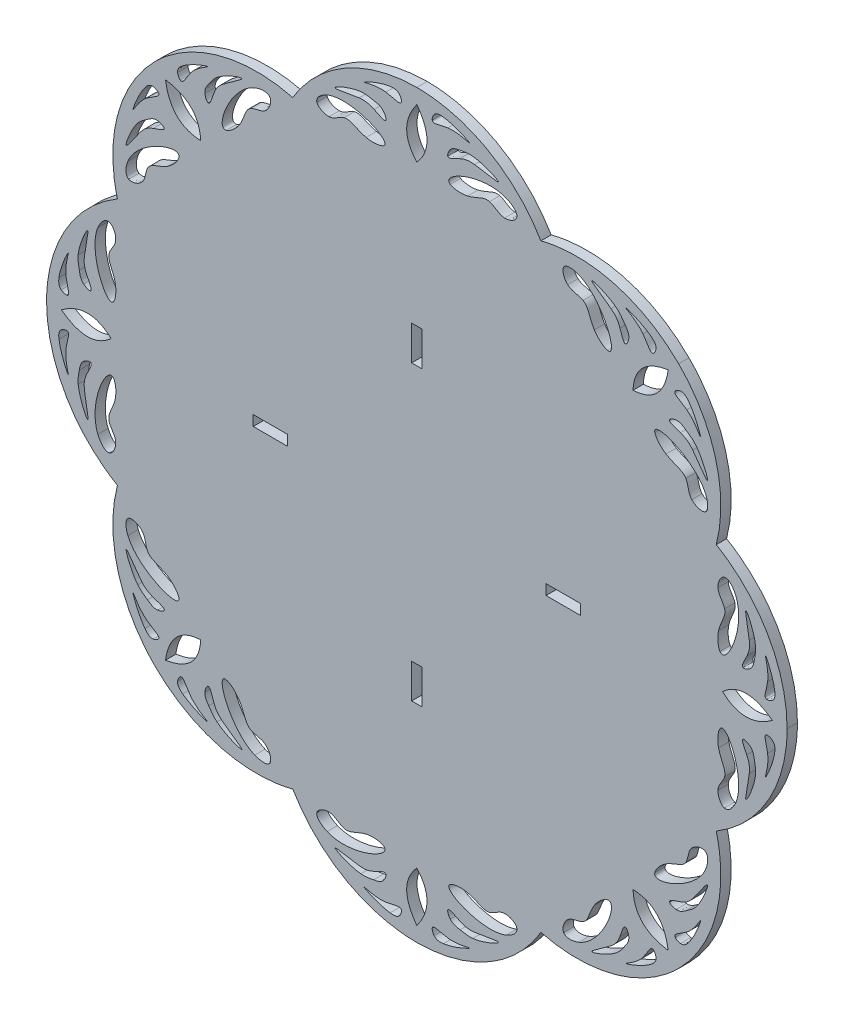
SolidWorks part; units mm, degrees
ref_plane "Plano frontal" through (0, 0, 0) normal (0, 0, 1) x (1, 0, 0)
ref_plane "Plano superior" through (0, 0, 0) normal (0, 1, 0) x (1, 0, 0)
ref_plane "Plano direito" through (0, 0, 0) normal (1, 0, 0) x (0, 0, -1)
sketch "Model" plane through (0, 0, 0) normal (0, 0, 1) x (1, 0, 0)
  line L58 (25.0001, 60.0569) -> (31.6667, 60.0569)
  line L59 (31.6667, 60.0569) -> (31.6667, 62.0569)
  line L60 (31.6667, 62.0569) -> (25.0001, 62.0569)
  line L61 (25.0001, 62.0569) -> (25.0001, 60.0569)
  line L62 (1.0001, 86.0569) -> (1.0001, 92.7236)
  line L63 (1.0001, 92.7236) -> (-0.9999, 92.7236)
  line L64 (-0.9999, 92.7236) -> (-0.9999, 86.0569)
  line L65 (-0.9999, 86.0569) -> (1.0001, 86.0569)
  line L66 (-31.6666, 60.0569) -> (-24.9999, 60.0569)
  line L67 (-24.9999, 60.0569) -> (-24.9999, 62.0569)
  line L68 (-24.9999, 62.0569) -> (-31.6666, 62.0569)
  line L69 (-31.6666, 62.0569) -> (-31.6666, 60.0569)
  line L70 (1.0001, 29.3903) -> (1.0001, 36.057)
  line L71 (1.0001, 36.057) -> (-0.9999, 36.057)
  line L72 (-0.9999, 36.057) -> (-0.9999, 29.3903)
  line L73 (-0.9999, 29.3903) -> (1.0001, 29.3903)
  line L74 (57.9547, 37.0512) -> (57.9546, 37.0513)
  spline S270 degree 3 poles (-52.2509, 104.8151) (-51.0841, 105.7149) (-49.5495, 106.2377) (-50.0038, 106.8337) knots 0 0 0 0 0.166667 0.166667 0.166667 0.166667
  spline S271 degree 3 poles (-50.0038, 106.8337) (-50.1747, 107.0579) (-50.6271, 107.2925) (-51.0214, 107.3395) knots 0.166667 0.166667 0.166667 0.166667 0.333333 0.333333 0.333333 0.333333
  spline S272 degree 3 poles (-51.0214, 107.3395) (-51.675, 107.4175) (-52.1689, 106.9805) (-52.6361, 106.3699) knots 0.333333 0.333333 0.333333 0.333333 0.5 0.5 0.5 0.5
  spline S273 degree 3 poles (-52.6361, 106.3699) (-53.9612, 104.6382) (-55.0714, 101.5111) (-54.917, 101.5396) knots 0.5 0.5 0.5 0.5 0.666667 0.666667 0.666667 0.666667
  spline S274 degree 3 poles (-54.917, 101.5396) (-54.795, 101.5621) (-53.8823, 103.557) (-52.2509, 104.8151) knots 0.666667 0.666667 0.666667 0.666667 1 1 1 1
  spline S275 degree 3 poles (-52.0754, 93.2206) (-51.4239, 94.3293) (-49.6775, 94.4625) (-48.2286, 95.3916) knots 0 0 0 0 0.142857 0.142857 0.142857 0.142857
  spline S276 degree 3 poles (-48.2286, 95.3916) (-47.1296, 96.0963) (-46.2019, 97.2589) (-46.0576, 97.9434) knots 0.142857 0.142857 0.142857 0.142857 0.285714 0.285714 0.285714 0.285714
  spline S277 degree 3 poles (-46.0576, 97.9434) (-45.5709, 100.253) (-54.0055, 97.1175) (-55.9222, 92.4208) knots 0.285714 0.285714 0.285714 0.285714 0.428571 0.428571 0.428571 0.428571
  spline S278 degree 3 poles (-55.9222, 92.4208) (-56.4254, 91.1875) (-56.4794, 89.8466) (-55.7668, 89.4564) knots 0.428571 0.428571 0.428571 0.428571 0.571429 0.571429 0.571429 0.571429
  spline S279 degree 3 poles (-55.7668, 89.4564) (-55.1261, 89.1054) (-53.8656, 89.5232) (-53.218, 90.2498) knots 0.571429 0.571429 0.571429 0.571429 0.714286 0.714286 0.714286 0.714286
  spline S280 degree 3 poles (-53.218, 90.2498) (-52.4458, 91.1162) (-52.5449, 92.4217) (-52.0754, 93.2206) knots 0.714286 0.714286 0.714286 0.714286 1 1 1 1
  spline S281 degree 3 poles (-32.1751, 113.1209) (-31.3762, 113.5904) (-30.0707, 113.4913) (-29.2043, 114.2635) knots 0 0 0 0 0.142857 0.142857 0.142857 0.142857
  spline S282 degree 3 poles (-29.2043, 114.2635) (-28.4777, 114.9111) (-28.0598, 116.1716) (-28.4109, 116.8123) knots 0.142857 0.142857 0.142857 0.142857 0.285714 0.285714 0.285714 0.285714
  spline S283 degree 3 poles (-28.4109, 116.8123) (-28.8011, 117.5248) (-30.142, 117.4709) (-31.3753, 116.9677) knots 0.285714 0.285714 0.285714 0.285714 0.428571 0.428571 0.428571 0.428571
  spline S284 degree 3 poles (-31.3753, 116.9677) (-36.072, 115.051) (-39.2075, 106.6164) (-36.8979, 107.1032) knots 0.428571 0.428571 0.428571 0.428571 0.571429 0.571429 0.571429 0.571429
  spline S285 degree 3 poles (-36.8979, 107.1032) (-36.2135, 107.2473) (-35.0508, 108.1751) (-34.3461, 109.2741) knots 0.571429 0.571429 0.571429 0.571429 0.714286 0.714286 0.714286 0.714286
  spline S286 degree 3 poles (-34.3461, 109.2741) (-33.417, 110.7229) (-33.2838, 112.4693) (-32.1751, 113.1209) knots 0.714286 0.714286 0.714286 0.714286 1 1 1 1
  spline S287 degree 3 poles (-43.7696, 113.2964) (-42.5115, 114.9278) (-40.5165, 115.8405) (-40.4941, 115.9625) knots 0 0 0 0 0.166667 0.166667 0.166667 0.166667
  spline S288 degree 3 poles (-40.4941, 115.9625) (-40.4657, 116.1169) (-43.5927, 115.0068) (-45.3243, 113.6817) knots 0.166667 0.166667 0.166667 0.166667 0.333333 0.333333 0.333333 0.333333
  spline S289 degree 3 poles (-45.3243, 113.6817) (-45.9349, 113.2144) (-46.372, 112.7205) (-46.2941, 112.0669) knots 0.333333 0.333333 0.333333 0.333333 0.5 0.5 0.5 0.5
  spline S290 degree 3 poles (-46.2941, 112.0669) (-46.247, 111.6726) (-46.0124, 111.2202) (-45.7882, 111.0493) knots 0.5 0.5 0.5 0.5 0.666667 0.666667 0.666667 0.666667
  spline S291 degree 3 poles (-45.7882, 111.0493) (-45.1922, 110.595) (-44.6694, 112.1296) (-43.7696, 113.2964) knots 0.666667 0.666667 0.666667 0.666667 1 1 1 1
  spline S292 degree 3 poles (-65.3251, 52.6691) (-65.4687, 51.8708) (-65.6418, 51.1534) (-65.5495, 50.2005) knots 0 0 0 0 0.125 0.125 0.125 0.125
  spline S293 degree 3 poles (-65.5495, 50.2005) (-65.3525, 48.1667) (-63.9461, 45.0602) (-63.6955, 45.2451) knots 0.125 0.125 0.125 0.125 0.25 0.25 0.25 0.25
  spline S294 degree 3 poles (-63.6955, 45.2451) (-63.4739, 45.4086) (-64.1556, 48.1441) (-64.3418, 49.8773) knots 0.25 0.25 0.25 0.25 0.375 0.375 0.375 0.375
  spline S295 degree 3 poles (-64.3418, 49.8773) (-64.4592, 50.9701) (-64.3797, 51.6644) (-63.857, 52.786) knots 0.375 0.375 0.375 0.375 0.5 0.5 0.5 0.5
  spline S296 degree 3 poles (-63.857, 52.786) (-63.4373, 53.6866) (-62.7316, 54.8628) (-63.1568, 55.0482) knots 0.5 0.5 0.5 0.5 0.625 0.625 0.625 0.625
  spline S297 degree 3 poles (-63.1568, 55.0482) (-63.4115, 55.1593) (-64.0717, 54.9149) (-64.4915, 54.5685) knots 0.625 0.625 0.625 0.625 0.75 0.75 0.75 0.75
  spline S298 degree 3 poles (-64.4915, 54.5685) (-65.1055, 54.062) (-65.205, 53.3372) (-65.3251, 52.6691) knots 0.75 0.75 0.75 0.75 1 1 1 1
  spline S299 degree 3 poles (-65.3251, 69.4217) (-65.205, 68.7537) (-65.1055, 68.0289) (-64.4915, 67.5224) knots 0 0 0 0 0.125 0.125 0.125 0.125
  spline S300 degree 3 poles (-64.4915, 67.5224) (-64.0717, 67.176) (-63.4115, 66.9316) (-63.1568, 67.0427) knots 0.125 0.125 0.125 0.125 0.25 0.25 0.25 0.25
  spline S301 degree 3 poles (-63.1568, 67.0427) (-62.7316, 67.2281) (-63.4373, 68.4042) (-63.857, 69.3049) knots 0.25 0.25 0.25 0.25 0.375 0.375 0.375 0.375
  spline S302 degree 3 poles (-63.857, 69.3049) (-64.3797, 70.4264) (-64.4592, 71.1208) (-64.3418, 72.2135) knots 0.375 0.375 0.375 0.375 0.5 0.5 0.5 0.5
  spline S303 degree 3 poles (-64.3418, 72.2135) (-64.1556, 73.9468) (-63.4739, 76.6823) (-63.6955, 76.8458) knots 0.5 0.5 0.5 0.5 0.625 0.625 0.625 0.625
  spline S304 degree 3 poles (-63.6955, 76.8458) (-63.9461, 77.0307) (-65.3525, 73.9242) (-65.5495, 71.8904) knots 0.625 0.625 0.625 0.625 0.75 0.75 0.75 0.75
  spline S305 degree 3 poles (-65.5495, 71.8904) (-65.6418, 70.9375) (-65.4687, 70.2201) (-65.3251, 69.4217) knots 0.75 0.75 0.75 0.75 1 1 1 1
  spline S306 degree 3 poles (-43.7696, 8.7945) (-44.6694, 9.9613) (-45.1922, 11.4959) (-45.7882, 11.0416) knots 0 0 0 0 0.166667 0.166667 0.166667 0.166667
  spline S307 degree 3 poles (-45.7882, 11.0416) (-46.0124, 10.8707) (-46.247, 10.4182) (-46.2941, 10.0239) knots 0.166667 0.166667 0.166667 0.166667 0.333333 0.333333 0.333333 0.333333
  spline S308 degree 3 poles (-46.2941, 10.0239) (-46.372, 9.3704) (-45.9349, 8.8765) (-45.3243, 8.4092) knots 0.333333 0.333333 0.333333 0.333333 0.5 0.5 0.5 0.5
  spline S309 degree 3 poles (-45.3243, 8.4092) (-43.5927, 7.0841) (-40.4657, 5.974) (-40.4941, 6.1284) knots 0.5 0.5 0.5 0.5 0.666667 0.666667 0.666667 0.666667
  spline S310 degree 3 poles (-40.4941, 6.1284) (-40.5165, 6.2504) (-42.5115, 7.163) (-43.7696, 8.7945) knots 0.666667 0.666667 0.666667 0.666667 1 1 1 1
  spline S311 degree 3 poles (-32.1751, 8.97) (-33.2838, 9.6215) (-33.417, 11.368) (-34.3461, 12.8168) knots 0 0 0 0 0.142857 0.142857 0.142857 0.142857
  spline S312 degree 3 poles (-34.3461, 12.8168) (-35.0508, 13.9158) (-36.2135, 14.8436) (-36.8979, 14.9877) knots 0.142857 0.142857 0.142857 0.142857 0.285714 0.285714 0.285714 0.285714
  spline S313 degree 3 poles (-36.8979, 14.9877) (-39.2075, 15.4745) (-36.072, 7.0399) (-31.3753, 5.1232) knots 0.285714 0.285714 0.285714 0.285714 0.428571 0.428571 0.428571 0.428571
  spline S314 degree 3 poles (-31.3753, 5.1232) (-30.142, 4.6199) (-28.8011, 4.5661) (-28.4109, 5.2785) knots 0.428571 0.428571 0.428571 0.428571 0.571429 0.571429 0.571429 0.571429
  spline S315 degree 3 poles (-28.4109, 5.2785) (-28.0598, 5.9193) (-28.4777, 7.1798) (-29.2043, 7.8274) knots 0.571429 0.571429 0.571429 0.571429 0.714286 0.714286 0.714286 0.714286
  spline S316 degree 3 poles (-29.2043, 7.8274) (-30.0707, 8.5996) (-31.3762, 8.5005) (-32.1751, 8.97) knots 0.714286 0.714286 0.714286 0.714286 1 1 1 1
  spline S317 degree 3 poles (-52.0754, 28.8702) (-52.5449, 29.6692) (-52.4458, 30.9747) (-53.218, 31.8411) knots 0 0 0 0 0.142857 0.142857 0.142857 0.142857
  spline S318 degree 3 poles (-53.218, 31.8411) (-53.8656, 32.5677) (-55.1261, 32.9855) (-55.7668, 32.6345) knots 0.142857 0.142857 0.142857 0.142857 0.285714 0.285714 0.285714 0.285714
  spline S319 degree 3 poles (-55.7668, 32.6345) (-56.4794, 32.2443) (-56.4254, 30.9034) (-55.9222, 29.6701) knots 0.285714 0.285714 0.285714 0.285714 0.428571 0.428571 0.428571 0.428571
  spline S320 degree 3 poles (-55.9222, 29.6701) (-54.0055, 24.9733) (-45.5709, 21.8379) (-46.0576, 24.1474) knots 0.428571 0.428571 0.428571 0.428571 0.571429 0.571429 0.571429 0.571429
  spline S321 degree 3 poles (-46.0576, 24.1474) (-46.2019, 24.8319) (-47.1296, 25.9946) (-48.2286, 26.6993) knots 0.571429 0.571429 0.571429 0.571429 0.714286 0.714286 0.714286 0.714286
  spline S322 degree 3 poles (-48.2286, 26.6993) (-49.6775, 27.6284) (-51.4239, 27.7616) (-52.0754, 28.8702) knots 0.714286 0.714286 0.714286 0.714286 1 1 1 1
  spline S323 degree 3 poles (-52.2509, 17.2758) (-53.8823, 18.5339) (-54.795, 20.5288) (-54.917, 20.5513) knots 0 0 0 0 0.166667 0.166667 0.166667 0.166667
  spline S324 degree 3 poles (-54.917, 20.5513) (-55.0714, 20.5797) (-53.9612, 17.4526) (-52.6361, 15.721) knots 0.166667 0.166667 0.166667 0.166667 0.333333 0.333333 0.333333 0.333333
  spline S325 degree 3 poles (-52.6361, 15.721) (-52.1689, 15.1104) (-51.675, 14.6734) (-51.0214, 14.7514) knots 0.333333 0.333333 0.333333 0.333333 0.5 0.5 0.5 0.5
  spline S326 degree 3 poles (-51.0214, 14.7514) (-50.6271, 14.7984) (-50.1747, 15.033) (-50.0038, 15.2572) knots 0.5 0.5 0.5 0.5 0.666667 0.666667 0.666667 0.666667
  spline S327 degree 3 poles (-50.0038, 15.2572) (-49.5495, 15.8531) (-51.0841, 16.376) (-52.2509, 17.2758) knots 0.666667 0.666667 0.666667 0.666667 1 1 1 1
  spline S328 degree 3 poles (8.3763, -4.2797) (9.1747, -4.4233) (9.8921, -4.5965) (10.845, -4.5042) knots 0 0 0 0 0.125 0.125 0.125 0.125
  spline S329 degree 3 poles (10.845, -4.5042) (12.8788, -4.3071) (15.9853, -2.9007) (15.8004, -2.65) knots 0.125 0.125 0.125 0.125 0.25 0.25 0.25 0.25
  spline S330 degree 3 poles (15.8004, -2.65) (15.6369, -2.4285) (12.9014, -3.1101) (11.1681, -3.2964) knots 0.25 0.25 0.25 0.25 0.375 0.375 0.375 0.375
  spline S331 degree 3 poles (11.1681, -3.2964) (10.0754, -3.4138) (9.3811, -3.3343) (8.2595, -2.8117) knots 0.375 0.375 0.375 0.375 0.5 0.5 0.5 0.5
  spline S332 degree 3 poles (8.2595, -2.8117) (7.3588, -2.3919) (6.1826, -1.6862) (5.9973, -2.1114) knots 0.5 0.5 0.5 0.5 0.625 0.625 0.625 0.625
  spline S333 degree 3 poles (5.9973, -2.1114) (5.8862, -2.3661) (6.1306, -3.0264) (6.477, -3.4461) knots 0.625 0.625 0.625 0.625 0.75 0.75 0.75 0.75
  spline S334 degree 3 poles (6.477, -3.4461) (6.9835, -4.0601) (7.7083, -4.1595) (8.3763, -4.2797) knots 0.75 0.75 0.75 0.75 1 1 1 1
  spline S335 degree 3 poles (-8.3762, -4.2797) (-7.7082, -4.1595) (-6.9834, -4.0601) (-6.4769, -3.4461) knots 0 0 0 0 0.125 0.125 0.125 0.125
  spline S336 degree 3 poles (-6.4769, -3.4461) (-6.1305, -3.0264) (-5.8861, -2.3661) (-5.9972, -2.1114) knots 0.125 0.125 0.125 0.125 0.25 0.25 0.25 0.25
  spline S337 degree 3 poles (-5.9972, -2.1114) (-6.1826, -1.6862) (-7.3587, -2.3919) (-8.2594, -2.8117) knots 0.25 0.25 0.25 0.25 0.375 0.375 0.375 0.375
  spline S338 degree 3 poles (-8.2594, -2.8117) (-9.3809, -3.3343) (-10.0753, -3.4138) (-11.1681, -3.2964) knots 0.375 0.375 0.375 0.375 0.5 0.5 0.5 0.5
  spline S339 degree 3 poles (-11.1681, -3.2964) (-12.9013, -3.1101) (-15.6368, -2.4285) (-15.8003, -2.65) knots 0.5 0.5 0.5 0.5 0.625 0.625 0.625 0.625
  spline S340 degree 3 poles (-15.8003, -2.65) (-15.9852, -2.9007) (-12.8787, -4.3071) (-10.8449, -4.5042) knots 0.625 0.625 0.625 0.625 0.75 0.75 0.75 0.75
  spline S341 degree 3 poles (-10.8449, -4.5042) (-9.892, -4.5965) (-9.1746, -4.4233) (-8.3762, -4.2797) knots 0.75 0.75 0.75 0.75 1 1 1 1
  spline S342 degree 3 poles (52.251, 17.2758) (51.0842, 16.376) (49.5496, 15.8531) (50.0039, 15.2572) knots 0 0 0 0 0.166667 0.166667 0.166667 0.166667
  spline S343 degree 3 poles (50.0039, 15.2572) (50.1748, 15.033) (50.6272, 14.7984) (51.0215, 14.7514) knots 0.166667 0.166667 0.166667 0.166667 0.333333 0.333333 0.333333 0.333333
  spline S344 degree 3 poles (51.0215, 14.7514) (51.6751, 14.6734) (52.169, 15.1104) (52.6362, 15.721) knots 0.333333 0.333333 0.333333 0.333333 0.5 0.5 0.5 0.5
  spline S345 degree 3 poles (52.6362, 15.721) (53.9613, 17.4526) (55.0715, 20.5797) (54.9171, 20.5513) knots 0.5 0.5 0.5 0.5 0.666667 0.666667 0.666667 0.666667
  spline S346 degree 3 poles (54.9171, 20.5513) (54.7951, 20.5288) (53.8825, 18.5339) (52.251, 17.2758) knots 0.666667 0.666667 0.666667 0.666667 1 1 1 1
  spline S347 degree 3 poles (52.0755, 28.8702) (51.424, 27.7616) (49.6776, 27.6284) (48.2287, 26.6993) knots 0 0 0 0 0.142857 0.142857 0.142857 0.142857
  spline S348 degree 3 poles (48.2287, 26.6993) (47.1297, 25.9946) (46.202, 24.8319) (46.0577, 24.1474) knots 0.142857 0.142857 0.142857 0.142857 0.285714 0.285714 0.285714 0.285714
  spline S349 degree 3 poles (46.0577, 24.1474) (45.571, 21.8379) (54.0056, 24.9733) (55.9223, 29.6701) knots 0.285714 0.285714 0.285714 0.285714 0.428571 0.428571 0.428571 0.428571
  spline S350 degree 3 poles (55.9223, 29.6701) (56.4256, 30.9034) (56.4795, 32.2443) (55.7669, 32.6345) knots 0.428571 0.428571 0.428571 0.428571 0.571429 0.571429 0.571429 0.571429
  spline S351 degree 3 poles (55.7669, 32.6345) (55.1262, 32.9855) (53.8657, 32.5677) (53.2181, 31.8411) knots 0.571429 0.571429 0.571429 0.571429 0.714286 0.714286 0.714286 0.714286
  spline S352 degree 3 poles (53.2181, 31.8411) (52.4459, 30.9747) (52.545, 29.6692) (52.0755, 28.8702) knots 0.714286 0.714286 0.714286 0.714286 1 1 1 1
  spline S353 degree 3 poles (32.1752, 8.97) (31.3763, 8.5005) (30.0709, 8.5996) (29.2044, 7.8274) knots 0 0 0 0 0.142857 0.142857 0.142857 0.142857
  spline S354 degree 3 poles (29.2044, 7.8274) (28.4778, 7.1798) (28.0599, 5.9193) (28.4109, 5.2785) knots 0.142857 0.142857 0.142857 0.142857 0.285714 0.285714 0.285714 0.285714
  spline S355 degree 3 poles (28.4109, 5.2785) (28.8012, 4.5661) (30.1421, 4.6199) (31.3754, 5.1232) knots 0.285714 0.285714 0.285714 0.285714 0.428571 0.428571 0.428571 0.428571
  spline S356 degree 3 poles (31.3754, 5.1232) (36.0721, 7.0399) (39.2076, 15.4745) (36.898, 14.9877) knots 0.428571 0.428571 0.428571 0.428571 0.571429 0.571429 0.571429 0.571429
  spline S357 degree 3 poles (36.898, 14.9877) (36.2136, 14.8436) (35.0509, 13.9158) (34.3462, 12.8168) knots 0.571429 0.571429 0.571429 0.571429 0.714286 0.714286 0.714286 0.714286
  spline S358 degree 3 poles (34.3462, 12.8168) (33.417, 11.368) (33.2839, 9.6215) (32.1752, 8.97) knots 0.714286 0.714286 0.714286 0.714286 1 1 1 1
  spline S359 degree 3 poles (43.7697, 8.7945) (42.5116, 7.163) (40.5166, 6.2504) (40.4942, 6.1284) knots 0 0 0 0 0.166667 0.166667 0.166667 0.166667
  spline S360 degree 3 poles (40.4942, 6.1284) (40.4658, 5.974) (43.5928, 7.0841) (45.3244, 8.4092) knots 0.166667 0.166667 0.166667 0.166667 0.333333 0.333333 0.333333 0.333333
  spline S361 degree 3 poles (45.3244, 8.4092) (45.935, 8.8765) (46.3721, 9.3704) (46.2941, 10.0239) knots 0.333333 0.333333 0.333333 0.333333 0.5 0.5 0.5 0.5
  spline S362 degree 3 poles (46.2941, 10.0239) (46.2471, 10.4182) (46.0125, 10.8707) (45.7883, 11.0416) knots 0.5 0.5 0.5 0.5 0.666667 0.666667 0.666667 0.666667
  spline S363 degree 3 poles (45.7883, 11.0416) (45.1923, 11.4959) (44.6694, 9.9613) (43.7697, 8.7945) knots 0.666667 0.666667 0.666667 0.666667 1 1 1 1
  spline S364 degree 3 poles (65.3252, 69.4217) (65.4688, 70.2201) (65.6419, 70.9375) (65.5496, 71.8904) knots 0 0 0 0 0.125 0.125 0.125 0.125
  spline S365 degree 3 poles (65.5496, 71.8904) (65.3526, 73.9242) (63.9462, 77.0307) (63.6955, 76.8458) knots 0.125 0.125 0.125 0.125 0.25 0.25 0.25 0.25
  spline S366 degree 3 poles (63.6955, 76.8458) (63.474, 76.6823) (64.1556, 73.9468) (64.3419, 72.2135) knots 0.25 0.25 0.25 0.25 0.375 0.375 0.375 0.375
  spline S367 degree 3 poles (64.3419, 72.2135) (64.4593, 71.1208) (64.3798, 70.4264) (63.8571, 69.3049) knots 0.375 0.375 0.375 0.375 0.5 0.5 0.5 0.5
  spline S368 degree 3 poles (63.8571, 69.3049) (63.4373, 68.4042) (62.7317, 67.2281) (63.1569, 67.0427) knots 0.5 0.5 0.5 0.5 0.625 0.625 0.625 0.625
  spline S369 degree 3 poles (63.1569, 67.0427) (63.4116, 66.9316) (64.0718, 67.176) (64.4916, 67.5224) knots 0.625 0.625 0.625 0.625 0.75 0.75 0.75 0.75
  spline S370 degree 3 poles (64.4916, 67.5224) (65.1055, 68.0289) (65.2051, 68.7537) (65.3252, 69.4217) knots 0.75 0.75 0.75 0.75 1 1 1 1
  spline S371 degree 3 poles (65.3252, 52.6691) (65.2051, 53.3372) (65.1055, 54.062) (64.4916, 54.5685) knots 0 0 0 0 0.125 0.125 0.125 0.125
  spline S372 degree 3 poles (64.4916, 54.5685) (64.0718, 54.9149) (63.4116, 55.1593) (63.1569, 55.0482) knots 0.125 0.125 0.125 0.125 0.25 0.25 0.25 0.25
  spline S373 degree 3 poles (63.1569, 55.0482) (62.7317, 54.8628) (63.4373, 53.6866) (63.8571, 52.786) knots 0.25 0.25 0.25 0.25 0.375 0.375 0.375 0.375
  spline S374 degree 3 poles (63.8571, 52.786) (64.3798, 51.6644) (64.4593, 50.9701) (64.3419, 49.8773) knots 0.375 0.375 0.375 0.375 0.5 0.5 0.5 0.5
  spline S375 degree 3 poles (64.3419, 49.8773) (64.1556, 48.1441) (63.474, 45.4086) (63.6955, 45.2451) knots 0.5 0.5 0.5 0.5 0.625 0.625 0.625 0.625
  spline S376 degree 3 poles (63.6955, 45.2451) (63.9462, 45.0602) (65.3526, 48.1667) (65.5496, 50.2005) knots 0.625 0.625 0.625 0.625 0.75 0.75 0.75 0.75
  spline S377 degree 3 poles (65.5496, 50.2005) (65.6419, 51.1534) (65.4688, 51.8708) (65.3252, 52.6691) knots 0.75 0.75 0.75 0.75 1 1 1 1
  spline S378 degree 3 poles (43.7697, 113.2964) (44.6694, 112.1296) (45.1923, 110.595) (45.7883, 111.0493) knots 0 0 0 0 0.166667 0.166667 0.166667 0.166667
  spline S379 degree 3 poles (45.7883, 111.0493) (46.0125, 111.2202) (46.2471, 111.6726) (46.2941, 112.0669) knots 0.166667 0.166667 0.166667 0.166667 0.333333 0.333333 0.333333 0.333333
  spline S380 degree 3 poles (46.2941, 112.0669) (46.3721, 112.7205) (45.935, 113.2144) (45.3244, 113.6817) knots 0.333333 0.333333 0.333333 0.333333 0.5 0.5 0.5 0.5
  spline S381 degree 3 poles (45.3244, 113.6817) (43.5928, 115.0068) (40.4658, 116.1169) (40.4942, 115.9625) knots 0.5 0.5 0.5 0.5 0.666667 0.666667 0.666667 0.666667
  spline S382 degree 3 poles (40.4942, 115.9625) (40.5166, 115.8405) (42.5116, 114.9278) (43.7697, 113.2964) knots 0.666667 0.666667 0.666667 0.666667 1 1 1 1
  spline S383 degree 3 poles (32.1752, 113.1209) (33.2839, 112.4693) (33.417, 110.7229) (34.3462, 109.2741) knots 0 0 0 0 0.142857 0.142857 0.142857 0.142857
  spline S384 degree 3 poles (34.3462, 109.2741) (35.0509, 108.1751) (36.2136, 107.2473) (36.898, 107.1032) knots 0.142857 0.142857 0.142857 0.142857 0.285714 0.285714 0.285714 0.285714
  spline S385 degree 3 poles (36.898, 107.1032) (39.2076, 106.6164) (36.0721, 115.051) (31.3754, 116.9677) knots 0.285714 0.285714 0.285714 0.285714 0.428571 0.428571 0.428571 0.428571
  spline S386 degree 3 poles (31.3754, 116.9677) (30.1421, 117.4709) (28.8012, 117.5248) (28.4109, 116.8123) knots 0.428571 0.428571 0.428571 0.428571 0.571429 0.571429 0.571429 0.571429
  spline S387 degree 3 poles (28.4109, 116.8123) (28.0599, 116.1716) (28.4778, 114.9111) (29.2044, 114.2635) knots 0.571429 0.571429 0.571429 0.571429 0.714286 0.714286 0.714286 0.714286
  spline S388 degree 3 poles (29.2044, 114.2635) (30.0709, 113.4913) (31.3763, 113.5904) (32.1752, 113.1209) knots 0.714286 0.714286 0.714286 0.714286 1 1 1 1
  spline S389 degree 3 poles (52.0755, 93.2206) (52.545, 92.4217) (52.4459, 91.1162) (53.2181, 90.2498) knots 0 0 0 0 0.142857 0.142857 0.142857 0.142857
  spline S390 degree 3 poles (53.2181, 90.2498) (53.8657, 89.5232) (55.1262, 89.1054) (55.7669, 89.4564) knots 0.142857 0.142857 0.142857 0.142857 0.285714 0.285714 0.285714 0.285714
  spline S391 degree 3 poles (55.7669, 89.4564) (56.4795, 89.8466) (56.4256, 91.1875) (55.9223, 92.4208) knots 0.285714 0.285714 0.285714 0.285714 0.428571 0.428571 0.428571 0.428571
  spline S392 degree 3 poles (55.9223, 92.4208) (54.0056, 97.1175) (45.571, 100.253) (46.0577, 97.9434) knots 0.428571 0.428571 0.428571 0.428571 0.571429 0.571429 0.571429 0.571429
  spline S393 degree 3 poles (46.0577, 97.9434) (46.202, 97.2589) (47.1297, 96.0963) (48.2287, 95.3916) knots 0.571429 0.571429 0.571429 0.571429 0.714286 0.714286 0.714286 0.714286
  spline S394 degree 3 poles (48.2287, 95.3916) (49.6776, 94.4625) (51.424, 94.3293) (52.0755, 93.2206) knots 0.714286 0.714286 0.714286 0.714286 1 1 1 1
  spline S395 degree 3 poles (52.251, 104.8151) (53.8825, 103.557) (54.7951, 101.5621) (54.9171, 101.5396) knots 0 0 0 0 0.166667 0.166667 0.166667 0.166667
  spline S396 degree 3 poles (54.9171, 101.5396) (55.0715, 101.5111) (53.9613, 104.6382) (52.6362, 106.3699) knots 0.166667 0.166667 0.166667 0.166667 0.333333 0.333333 0.333333 0.333333
  spline S397 degree 3 poles (52.6362, 106.3699) (52.169, 106.9805) (51.6751, 107.4175) (51.0215, 107.3395) knots 0.333333 0.333333 0.333333 0.333333 0.5 0.5 0.5 0.5
  spline S398 degree 3 poles (51.0215, 107.3395) (50.6272, 107.2925) (50.1748, 107.0579) (50.0039, 106.8337) knots 0.5 0.5 0.5 0.5 0.666667 0.666667 0.666667 0.666667
  spline S399 degree 3 poles (50.0039, 106.8337) (49.5496, 106.2377) (51.0842, 105.7149) (52.251, 104.8151) knots 0.666667 0.666667 0.666667 0.666667 1 1 1 1
  spline S400 degree 3 poles (-8.3762, 126.3706) (-9.1746, 126.5142) (-9.892, 126.6873) (-10.8449, 126.5951) knots 0 0 0 0 0.125 0.125 0.125 0.125
  spline S401 degree 3 poles (-10.8449, 126.5951) (-12.8787, 126.398) (-15.9852, 124.9916) (-15.8003, 124.7409) knots 0.125 0.125 0.125 0.125 0.25 0.25 0.25 0.25
  spline S402 degree 3 poles (-15.8003, 124.7409) (-15.6368, 124.5194) (-12.9013, 125.201) (-11.1681, 125.3873) knots 0.25 0.25 0.25 0.25 0.375 0.375 0.375 0.375
  spline S403 degree 3 poles (-11.1681, 125.3873) (-10.0753, 125.5047) (-9.3809, 125.4252) (-8.2594, 124.9025) knots 0.375 0.375 0.375 0.375 0.5 0.5 0.5 0.5
  spline S404 degree 3 poles (-8.2594, 124.9025) (-7.3587, 124.4828) (-6.1826, 123.7771) (-5.9972, 124.2023) knots 0.5 0.5 0.5 0.5 0.625 0.625 0.625 0.625
  spline S405 degree 3 poles (-5.9972, 124.2023) (-5.8861, 124.457) (-6.1305, 125.1173) (-6.4769, 125.537) knots 0.625 0.625 0.625 0.625 0.75 0.75 0.75 0.75
  spline S406 degree 3 poles (-6.4769, 125.537) (-6.9834, 126.151) (-7.7082, 126.2504) (-8.3762, 126.3706) knots 0.75 0.75 0.75 0.75 1 1 1 1
  spline S407 degree 3 poles (8.3763, 126.3706) (7.7083, 126.2504) (6.9835, 126.151) (6.477, 125.537) knots 0 0 0 0 0.125 0.125 0.125 0.125
  spline S408 degree 3 poles (6.477, 125.537) (6.1306, 125.1173) (5.8862, 124.457) (5.9973, 124.2023) knots 0.125 0.125 0.125 0.125 0.25 0.25 0.25 0.25
  spline S409 degree 3 poles (5.9973, 124.2023) (6.1826, 123.7771) (7.3588, 124.4828) (8.2595, 124.9025) knots 0.25 0.25 0.25 0.25 0.375 0.375 0.375 0.375
  spline S410 degree 3 poles (8.2595, 124.9025) (9.3811, 125.4252) (10.0754, 125.5047) (11.1681, 125.3873) knots 0.375 0.375 0.375 0.375 0.5 0.5 0.5 0.5
  spline S411 degree 3 poles (11.1681, 125.3873) (12.9014, 125.201) (15.6369, 124.5194) (15.8004, 124.7409) knots 0.5 0.5 0.5 0.5 0.625 0.625 0.625 0.625
  spline S412 degree 3 poles (15.8004, 124.7409) (15.9853, 124.9916) (12.8788, 126.398) (10.845, 126.5951) knots 0.625 0.625 0.625 0.625 0.75 0.75 0.75 0.75
  spline S413 degree 3 poles (10.845, 126.5951) (9.8921, 126.6873) (9.1747, 126.5142) (8.3763, 126.3706) knots 0.75 0.75 0.75 0.75 1 1 1 1
  spline S414 degree 3 poles (5.9973, 128.9422) (8.0405, 129.2063) (10.0964, 128.4409) (10.1986, 128.5114) knots 0 0 0 0 0.166667 0.166667 0.166667 0.166667
  spline S415 degree 3 poles (10.1986, 128.5114) (10.3278, 128.6004) (7.3317, 130.0266) (5.1703, 130.3141) knots 0.166667 0.166667 0.166667 0.166667 0.333333 0.333333 0.333333 0.333333
  spline S416 degree 3 poles (5.1703, 130.3141) (4.4081, 130.4154) (3.7498, 130.3752) (3.3428, 129.8579) knots 0.333333 0.333333 0.333333 0.333333 0.5 0.5 0.5 0.5
  spline S417 degree 3 poles (3.3428, 129.8579) (3.0973, 129.5458) (2.9432, 129.0601) (2.9809, 128.7807) knots 0.5 0.5 0.5 0.5 0.666667 0.666667 0.666667 0.666667
  spline S418 degree 3 poles (2.9809, 128.7807) (3.0812, 128.038) (4.536, 128.7534) (5.9973, 128.9422) knots 0.666667 0.666667 0.666667 0.666667 1 1 1 1
  spline S419 degree 3 poles (14.0716, 120.6196) (14.9685, 120.3867) (15.8216, 119.3935) (16.9803, 119.3269) knots 0 0 0 0 0.142857 0.142857 0.142857 0.142857
  spline S420 degree 3 poles (16.9803, 119.3269) (17.952, 119.271) (19.1388, 119.8669) (19.3437, 120.5681) knots 0.142857 0.142857 0.142857 0.142857 0.285714 0.285714 0.285714 0.285714
  spline S421 degree 3 poles (19.3437, 120.5681) (19.5715, 121.3479) (18.5852, 122.2579) (17.3573, 122.7742) knots 0.285714 0.285714 0.285714 0.285714 0.428571 0.428571 0.428571 0.428571
  spline S422 degree 3 poles (17.3573, 122.7742) (12.6809, 124.7399) (4.4997, 120.9929) (6.477, 119.704) knots 0.428571 0.428571 0.428571 0.428571 0.571429 0.571429 0.571429 0.571429
  spline S423 degree 3 poles (6.477, 119.704) (7.0629, 119.322) (8.5411, 119.1558) (9.8165, 119.4346) knots 0.571429 0.571429 0.571429 0.571429 0.714286 0.714286 0.714286 0.714286
  spline S424 degree 3 poles (9.8165, 119.4346) (11.498, 119.8022) (12.827, 120.9429) (14.0716, 120.6196) knots 0.714286 0.714286 0.714286 0.714286 1 1 1 1
  spline S425 degree 3 poles (-14.0715, 120.6196) (-12.8269, 120.9429) (-11.4979, 119.8022) (-9.8164, 119.4346) knots 0 0 0 0 0.142857 0.142857 0.142857 0.142857
  spline S426 degree 3 poles (-9.8164, 119.4346) (-8.541, 119.1558) (-7.0628, 119.322) (-6.4769, 119.704) knots 0.142857 0.142857 0.142857 0.142857 0.285714 0.285714 0.285714 0.285714
  spline S427 degree 3 poles (-6.4769, 119.704) (-4.4996, 120.9929) (-12.6808, 124.7399) (-17.3572, 122.7742) knots 0.285714 0.285714 0.285714 0.285714 0.428571 0.428571 0.428571 0.428571
  spline S428 degree 3 poles (-17.3572, 122.7742) (-18.5851, 122.2579) (-19.5714, 121.3479) (-19.3436, 120.5681) knots 0.428571 0.428571 0.428571 0.428571 0.571429 0.571429 0.571429 0.571429
  spline S429 degree 3 poles (-19.3436, 120.5681) (-19.1387, 119.8669) (-17.9519, 119.271) (-16.9802, 119.3269) knots 0.571429 0.571429 0.571429 0.571429 0.714286 0.714286 0.714286 0.714286
  spline S430 degree 3 poles (-16.9802, 119.3269) (-15.8215, 119.3935) (-14.9684, 120.3867) (-14.0715, 120.6196) knots 0.714286 0.714286 0.714286 0.714286 1 1 1 1
  spline S431 degree 3 poles (-5.9972, 128.9422) (-4.5359, 128.7534) (-3.0811, 128.038) (-2.9808, 128.7807) knots 0 0 0 0 0.166667 0.166667 0.166667 0.166667
  spline S432 degree 3 poles (-2.9808, 128.7807) (-2.9431, 129.0601) (-3.0972, 129.5458) (-3.3427, 129.8579) knots 0.166667 0.166667 0.166667 0.166667 0.333333 0.333333 0.333333 0.333333
  spline S433 degree 3 poles (-3.3427, 129.8579) (-3.7497, 130.3752) (-4.408, 130.4154) (-5.1701, 130.3141) knots 0.333333 0.333333 0.333333 0.333333 0.5 0.5 0.5 0.5
  spline S434 degree 3 poles (-5.1701, 130.3141) (-7.3316, 130.0266) (-10.3278, 128.6004) (-10.1985, 128.5114) knots 0.5 0.5 0.5 0.5 0.666667 0.666667 0.666667 0.666667
  spline S435 degree 3 poles (-10.1985, 128.5114) (-10.0963, 128.4409) (-8.0404, 129.2063) (-5.9972, 128.9422) knots 0.666667 0.666667 0.666667 0.666667 1 1 1 1
  spline S436 degree 3 poles (52.1148, 101.3144) (51.5575, 101.7018) (50.9746, 102.1439) (50.1823, 102.068) knots 0 0 0 0 0.125 0.125 0.125 0.125
  spline S437 degree 3 poles (50.1823, 102.068) (49.6406, 102.0161) (49.0009, 101.722) (48.8994, 101.4634) knots 0.125 0.125 0.125 0.125 0.25 0.25 0.25 0.25
  spline S438 degree 3 poles (48.8994, 101.4634) (48.7298, 101.0317) (50.0605, 100.6989) (50.9942, 100.3589) knots 0.25 0.25 0.25 0.25 0.375 0.375 0.375 0.375
  spline S439 degree 3 poles (50.9942, 100.3589) (52.1568, 99.9355) (52.704, 99.5007) (53.3937, 98.645) knots 0.375 0.375 0.375 0.375 0.5 0.5 0.5 0.5
  spline S440 degree 3 poles (53.3937, 98.645) (54.4875, 97.2877) (55.9398, 94.8714) (56.2121, 94.9124) knots 0.5 0.5 0.5 0.5 0.625 0.625 0.625 0.625
  spline S441 degree 3 poles (56.2121, 94.9124) (56.52, 94.9589) (55.318, 98.15) (54.0191, 99.7275) knots 0.625 0.625 0.625 0.625 0.75 0.75 0.75 0.75
  spline S442 degree 3 poles (54.0191, 99.7275) (53.4106, 100.4665) (52.781, 100.8514) (52.1148, 101.3144) knots 0.75 0.75 0.75 0.75 1 1 1 1
  spline S443 degree 3 poles (40.269, 113.1602) (39.806, 113.8263) (39.4212, 114.456) (38.6821, 115.0645) knots 0 0 0 0 0.125 0.125 0.125 0.125
  spline S444 degree 3 poles (38.6821, 115.0645) (37.1046, 116.3633) (33.9135, 117.5655) (33.867, 117.2575) knots 0.125 0.125 0.125 0.125 0.25 0.25 0.25 0.25
  spline S445 degree 3 poles (33.867, 117.2575) (33.826, 116.9852) (36.2423, 115.533) (37.5996, 114.439) knots 0.25 0.25 0.25 0.25 0.375 0.375 0.375 0.375
  spline S446 degree 3 poles (37.5996, 114.439) (38.4553, 113.7494) (38.8901, 113.2022) (39.3135, 112.0396) knots 0.375 0.375 0.375 0.375 0.5 0.5 0.5 0.5
  spline S447 degree 3 poles (39.3135, 112.0396) (39.6536, 111.1058) (39.9863, 109.7752) (40.418, 109.9448) knots 0.5 0.5 0.5 0.5 0.625 0.625 0.625 0.625
  spline S448 degree 3 poles (40.418, 109.9448) (40.6766, 110.0463) (40.9707, 110.686) (41.0226, 111.2277) knots 0.625 0.625 0.625 0.625 0.75 0.75 0.75 0.75
  spline S449 degree 3 poles (41.0226, 111.2277) (41.0986, 112.02) (40.6564, 112.6029) (40.269, 113.1602) knots 0.75 0.75 0.75 0.75 1 1 1 1
  spline S450 degree 3 poles (67.8969, 55.0482) (68.1609, 53.005) (67.3956, 50.9491) (67.466, 50.8469) knots 0 0 0 0 0.166667 0.166667 0.166667 0.166667
  spline S451 degree 3 poles (67.466, 50.8469) (67.555, 50.7176) (68.9812, 53.7138) (69.2687, 55.8753) knots 0.166667 0.166667 0.166667 0.166667 0.333333 0.333333 0.333333 0.333333
  spline S452 degree 3 poles (69.2687, 55.8753) (69.37, 56.6374) (69.3298, 57.2957) (68.8125, 57.7027) knots 0.333333 0.333333 0.333333 0.333333 0.5 0.5 0.5 0.5
  spline S453 degree 3 poles (68.8125, 57.7027) (68.5005, 57.9482) (68.0147, 58.1023) (67.7353, 58.0646) knots 0.5 0.5 0.5 0.5 0.666667 0.666667 0.666667 0.666667
  spline S454 degree 3 poles (67.7353, 58.0646) (66.9926, 57.9644) (67.708, 56.5095) (67.8969, 55.0482) knots 0.666667 0.666667 0.666667 0.666667 1 1 1 1
  spline S455 degree 3 poles (59.5742, 46.9738) (59.3413, 46.0769) (58.3481, 45.2239) (58.2815, 44.0652) knots 0 0 0 0 0.142857 0.142857 0.142857 0.142857
  spline S456 degree 3 poles (58.2815, 44.0652) (58.2256, 43.0934) (58.8215, 41.9067) (59.5227, 41.7018) knots 0.142857 0.142857 0.142857 0.142857 0.285714 0.285714 0.285714 0.285714
  spline S457 degree 3 poles (59.5227, 41.7018) (60.3025, 41.474) (61.2125, 42.4603) (61.7287, 43.6882) knots 0.285714 0.285714 0.285714 0.285714 0.428571 0.428571 0.428571 0.428571
  spline S458 degree 3 poles (61.7287, 43.6882) (63.6946, 48.3646) (59.9475, 56.5458) (58.6585, 54.5685) knots 0.428571 0.428571 0.428571 0.428571 0.571429 0.571429 0.571429 0.571429
  spline S459 degree 3 poles (58.6585, 54.5685) (58.2766, 53.9826) (58.1105, 52.5044) (58.3892, 51.229) knots 0.571429 0.571429 0.571429 0.571429 0.714286 0.714286 0.714286 0.714286
  spline S460 degree 3 poles (58.3892, 51.229) (58.7568, 49.5475) (59.8975, 48.2185) (59.5742, 46.9738) knots 0.714286 0.714286 0.714286 0.714286 1 1 1 1
  spline S461 degree 3 poles (59.5742, 75.1171) (59.8975, 73.8724) (58.7568, 72.5434) (58.3892, 70.8619) knots 0 0 0 0 0.142857 0.142857 0.142857 0.142857
  spline S462 degree 3 poles (58.3892, 70.8619) (58.1105, 69.5865) (58.2766, 68.1083) (58.6585, 67.5224) knots 0.142857 0.142857 0.142857 0.142857 0.285714 0.285714 0.285714 0.285714
  spline S463 degree 3 poles (58.6585, 67.5224) (59.9475, 65.5451) (63.6946, 73.7263) (61.7287, 78.4027) knots 0.285714 0.285714 0.285714 0.285714 0.428571 0.428571 0.428571 0.428571
  spline S464 degree 3 poles (61.7287, 78.4027) (61.2125, 79.6306) (60.3025, 80.6169) (59.5227, 80.3891) knots 0.428571 0.428571 0.428571 0.428571 0.571429 0.571429 0.571429 0.571429
  spline S465 degree 3 poles (59.5227, 80.3891) (58.8215, 80.1842) (58.2256, 78.9974) (58.2815, 78.0257) knots 0.571429 0.571429 0.571429 0.571429 0.714286 0.714286 0.714286 0.714286
  spline S466 degree 3 poles (58.2815, 78.0257) (58.3481, 76.867) (59.3413, 76.0139) (59.5742, 75.1171) knots 0.714286 0.714286 0.714286 0.714286 1 1 1 1
  spline S467 degree 3 poles (67.8969, 67.0427) (67.708, 65.5813) (66.9926, 64.1265) (67.7353, 64.0263) knots 0 0 0 0 0.166667 0.166667 0.166667 0.166667
  spline S468 degree 3 poles (67.7353, 64.0263) (68.0147, 63.9886) (68.5005, 64.1427) (68.8125, 64.3882) knots 0.166667 0.166667 0.166667 0.166667 0.333333 0.333333 0.333333 0.333333
  spline S469 degree 3 poles (68.8125, 64.3882) (69.3298, 64.7952) (69.37, 65.4535) (69.2687, 66.2156) knots 0.333333 0.333333 0.333333 0.333333 0.5 0.5 0.5 0.5
  spline S470 degree 3 poles (69.2687, 66.2156) (68.9812, 68.3771) (67.555, 71.3733) (67.466, 71.244) knots 0.5 0.5 0.5 0.5 0.666667 0.666667 0.666667 0.666667
  spline S471 degree 3 poles (67.466, 71.244) (67.3956, 71.1418) (68.1609, 69.0859) (67.8969, 67.0427) knots 0.666667 0.666667 0.666667 0.666667 1 1 1 1
  spline S472 degree 3 poles (40.269, 8.9306) (40.6564, 9.488) (41.0986, 10.0708) (41.0226, 10.8631) knots 0 0 0 0 0.125 0.125 0.125 0.125
  spline S473 degree 3 poles (41.0226, 10.8631) (40.9707, 11.4049) (40.6766, 12.0445) (40.418, 12.1461) knots 0.125 0.125 0.125 0.125 0.25 0.25 0.25 0.25
  spline S474 degree 3 poles (40.418, 12.1461) (39.9863, 12.3157) (39.6536, 10.9851) (39.3135, 10.0513) knots 0.25 0.25 0.25 0.25 0.375 0.375 0.375 0.375
  spline S475 degree 3 poles (39.3135, 10.0513) (38.8901, 8.8887) (38.4553, 8.3415) (37.5996, 7.6519) knots 0.375 0.375 0.375 0.375 0.5 0.5 0.5 0.5
  spline S476 degree 3 poles (37.5996, 7.6519) (36.2423, 6.5579) (33.826, 5.1056) (33.867, 4.8334) knots 0.5 0.5 0.5 0.5 0.625 0.625 0.625 0.625
  spline S477 degree 3 poles (33.867, 4.8334) (33.9135, 4.5254) (37.1046, 5.7276) (38.6821, 7.0264) knots 0.625 0.625 0.625 0.625 0.75 0.75 0.75 0.75
  spline S478 degree 3 poles (38.6821, 7.0264) (39.4212, 7.6348) (39.806, 8.2646) (40.269, 8.9306) knots 0.75 0.75 0.75 0.75 1 1 1 1
  spline S479 degree 3 poles (52.1148, 20.7765) (52.781, 21.2395) (53.4106, 21.6244) (54.0191, 22.3634) knots 0 0 0 0 0.125 0.125 0.125 0.125
  spline S480 degree 3 poles (54.0191, 22.3634) (55.318, 23.9409) (56.52, 27.132) (56.2121, 27.1784) knots 0.125 0.125 0.125 0.125 0.25 0.25 0.25 0.25
  spline S481 degree 3 poles (56.2121, 27.1784) (55.9398, 27.2195) (54.4875, 24.8032) (53.3937, 23.4459) knots 0.25 0.25 0.25 0.25 0.375 0.375 0.375 0.375
  spline S482 degree 3 poles (53.3937, 23.4459) (52.704, 22.5902) (52.1568, 22.1554) (50.9942, 21.732) knots 0.375 0.375 0.375 0.375 0.5 0.5 0.5 0.5
  spline S483 degree 3 poles (50.9942, 21.732) (50.0605, 21.392) (48.7298, 21.0592) (48.8994, 20.6275) knots 0.5 0.5 0.5 0.5 0.625 0.625 0.625 0.625
  spline S484 degree 3 poles (48.8994, 20.6275) (49.0009, 20.3689) (49.6406, 20.0748) (50.1823, 20.0229) knots 0.625 0.625 0.625 0.625 0.75 0.75 0.75 0.75
  spline S485 degree 3 poles (50.1823, 20.0229) (50.9746, 19.947) (51.5575, 20.3891) (52.1148, 20.7765) knots 0.75 0.75 0.75 0.75 1 1 1 1
  spline S486 degree 3 poles (-5.9972, -6.8514) (-8.0404, -7.1154) (-10.0963, -6.35) (-10.1985, -6.4205) knots 0 0 0 0 0.166667 0.166667 0.166667 0.166667
  spline S487 degree 3 poles (-10.1985, -6.4205) (-10.3278, -6.5096) (-7.3316, -7.9357) (-5.1701, -8.2232) knots 0.166667 0.166667 0.166667 0.166667 0.333333 0.333333 0.333333 0.333333
  spline S488 degree 3 poles (-5.1701, -8.2232) (-4.408, -8.3245) (-3.7497, -8.2843) (-3.3427, -7.767) knots 0.333333 0.333333 0.333333 0.333333 0.5 0.5 0.5 0.5
  spline S489 degree 3 poles (-3.3427, -7.767) (-3.0972, -7.455) (-2.9431, -6.9692) (-2.9808, -6.6898) knots 0.5 0.5 0.5 0.5 0.666667 0.666667 0.666667 0.666667
  spline S490 degree 3 poles (-2.9808, -6.6898) (-3.0811, -5.9472) (-4.5359, -6.6625) (-5.9972, -6.8514) knots 0.666667 0.666667 0.666667 0.666667 1 1 1 1
  spline S491 degree 3 poles (-14.0715, 1.4713) (-14.9684, 1.7042) (-15.8215, 2.6974) (-16.9802, 2.764) knots 0 0 0 0 0.142857 0.142857 0.142857 0.142857
  spline S492 degree 3 poles (-16.9802, 2.764) (-17.9519, 2.8198) (-19.1387, 2.224) (-19.3436, 1.5228) knots 0.142857 0.142857 0.142857 0.142857 0.285714 0.285714 0.285714 0.285714
  spline S493 degree 3 poles (-19.3436, 1.5228) (-19.5714, 0.743) (-18.5851, -0.1671) (-17.3572, -0.6833) knots 0.285714 0.285714 0.285714 0.285714 0.428571 0.428571 0.428571 0.428571
  spline S494 degree 3 poles (-17.3572, -0.6833) (-12.6808, -2.6491) (-4.4996, 1.098) (-6.4769, 2.3869) knots 0.428571 0.428571 0.428571 0.428571 0.571429 0.571429 0.571429 0.571429
  spline S495 degree 3 poles (-6.4769, 2.3869) (-7.0628, 2.7689) (-8.541, 2.935) (-9.8164, 2.6562) knots 0.571429 0.571429 0.571429 0.571429 0.714286 0.714286 0.714286 0.714286
  spline S496 degree 3 poles (-9.8164, 2.6562) (-11.4979, 2.2887) (-12.8269, 1.148) (-14.0715, 1.4713) knots 0.714286 0.714286 0.714286 0.714286 1 1 1 1
  spline S497 degree 3 poles (14.0716, 1.4713) (12.827, 1.148) (11.498, 2.2887) (9.8165, 2.6562) knots 0 0 0 0 0.142857 0.142857 0.142857 0.142857
  spline S498 degree 3 poles (9.8165, 2.6562) (8.5411, 2.935) (7.0629, 2.7689) (6.477, 2.3869) knots 0.142857 0.142857 0.142857 0.142857 0.285714 0.285714 0.285714 0.285714
  spline S499 degree 3 poles (6.477, 2.3869) (4.4997, 1.098) (12.6809, -2.6491) (17.3573, -0.6833) knots 0.285714 0.285714 0.285714 0.285714 0.428571 0.428571 0.428571 0.428571
  spline S500 degree 3 poles (17.3573, -0.6833) (18.5852, -0.1671) (19.5715, 0.743) (19.3437, 1.5228) knots 0.428571 0.428571 0.428571 0.428571 0.571429 0.571429 0.571429 0.571429
  spline S501 degree 3 poles (19.3437, 1.5228) (19.1388, 2.224) (17.952, 2.8198) (16.9803, 2.764) knots 0.571429 0.571429 0.571429 0.571429 0.714286 0.714286 0.714286 0.714286
  spline S502 degree 3 poles (16.9803, 2.764) (15.8216, 2.6974) (14.9685, 1.7042) (14.0716, 1.4713) knots 0.714286 0.714286 0.714286 0.714286 1 1 1 1
  spline S503 degree 3 poles (5.9973, -6.8514) (4.536, -6.6625) (3.0812, -5.9472) (2.9809, -6.6898) knots 0 0 0 0 0.166667 0.166667 0.166667 0.166667
  spline S504 degree 3 poles (2.9809, -6.6898) (2.9432, -6.9692) (3.0973, -7.455) (3.3428, -7.767) knots 0.166667 0.166667 0.166667 0.166667 0.333333 0.333333 0.333333 0.333333
  spline S505 degree 3 poles (3.3428, -7.767) (3.7498, -8.2843) (4.4081, -8.3245) (5.1703, -8.2232) knots 0.333333 0.333333 0.333333 0.333333 0.5 0.5 0.5 0.5
  spline S506 degree 3 poles (5.1703, -8.2232) (7.3317, -7.9357) (10.3278, -6.5096) (10.1986, -6.4205) knots 0.5 0.5 0.5 0.5 0.666667 0.666667 0.666667 0.666667
  spline S507 degree 3 poles (10.1986, -6.4205) (10.0964, -6.35) (8.0405, -7.1154) (5.9973, -6.8514) knots 0.666667 0.666667 0.666667 0.666667 1 1 1 1
  spline S508 degree 3 poles (-52.1147, 20.7765) (-51.5574, 20.3891) (-50.9745, 19.947) (-50.1822, 20.0229) knots 0 0 0 0 0.125 0.125 0.125 0.125
  spline S509 degree 3 poles (-50.1822, 20.0229) (-49.6405, 20.0748) (-49.0008, 20.3689) (-48.8993, 20.6275) knots 0.125 0.125 0.125 0.125 0.25 0.25 0.25 0.25
  spline S510 degree 3 poles (-48.8993, 20.6275) (-48.7297, 21.0592) (-50.0604, 21.392) (-50.9941, 21.732) knots 0.25 0.25 0.25 0.25 0.375 0.375 0.375 0.375
  spline S511 degree 3 poles (-50.9941, 21.732) (-52.1567, 22.1554) (-52.7039, 22.5902) (-53.3936, 23.4459) knots 0.375 0.375 0.375 0.375 0.5 0.5 0.5 0.5
  spline S512 degree 3 poles (-53.3936, 23.4459) (-54.4874, 24.8032) (-55.9397, 27.2195) (-56.212, 27.1784) knots 0.5 0.5 0.5 0.5 0.625 0.625 0.625 0.625
  spline S513 degree 3 poles (-56.212, 27.1784) (-56.5199, 27.132) (-55.3178, 23.9409) (-54.019, 22.3634) knots 0.625 0.625 0.625 0.625 0.75 0.75 0.75 0.75
  spline S514 degree 3 poles (-54.019, 22.3634) (-53.4106, 21.6244) (-52.7808, 21.2395) (-52.1147, 20.7765) knots 0.75 0.75 0.75 0.75 1 1 1 1
  spline S515 degree 3 poles (-40.2689, 8.9306) (-39.8059, 8.2646) (-39.4211, 7.6348) (-38.682, 7.0264) knots 0 0 0 0 0.125 0.125 0.125 0.125
  spline S516 degree 3 poles (-38.682, 7.0264) (-37.1045, 5.7276) (-33.9134, 4.5254) (-33.8669, 4.8334) knots 0.125 0.125 0.125 0.125 0.25 0.25 0.25 0.25
  spline S517 degree 3 poles (-33.8669, 4.8334) (-33.8259, 5.1056) (-36.2422, 6.5579) (-37.5995, 7.6519) knots 0.25 0.25 0.25 0.25 0.375 0.375 0.375 0.375
  spline S518 degree 3 poles (-37.5995, 7.6519) (-38.4552, 8.3415) (-38.89, 8.8887) (-39.3134, 10.0513) knots 0.375 0.375 0.375 0.375 0.5 0.5 0.5 0.5
  spline S519 degree 3 poles (-39.3134, 10.0513) (-39.6535, 10.9851) (-39.9862, 12.3157) (-40.4179, 12.1461) knots 0.5 0.5 0.5 0.5 0.625 0.625 0.625 0.625
  spline S520 degree 3 poles (-40.4179, 12.1461) (-40.6765, 12.0445) (-40.9706, 11.4049) (-41.0225, 10.8631) knots 0.625 0.625 0.625 0.625 0.75 0.75 0.75 0.75
  spline S521 degree 3 poles (-41.0225, 10.8631) (-41.0984, 10.0708) (-40.6563, 9.488) (-40.2689, 8.9306) knots 0.75 0.75 0.75 0.75 1 1 1 1
  spline S522 degree 3 poles (-67.8968, 67.0427) (-68.1608, 69.0859) (-67.3954, 71.1418) (-67.4659, 71.244) knots 0 0 0 0 0.166667 0.166667 0.166667 0.166667
  spline S523 degree 3 poles (-67.4659, 71.244) (-67.5549, 71.3733) (-68.9811, 68.3771) (-69.2686, 66.2156) knots 0.166667 0.166667 0.166667 0.166667 0.333333 0.333333 0.333333 0.333333
  spline S524 degree 3 poles (-69.2686, 66.2156) (-69.3699, 65.4535) (-69.3297, 64.7952) (-68.8125, 64.3882) knots 0.333333 0.333333 0.333333 0.333333 0.5 0.5 0.5 0.5
  spline S525 degree 3 poles (-68.8125, 64.3882) (-68.5004, 64.1427) (-68.0146, 63.9886) (-67.7352, 64.0263) knots 0.5 0.5 0.5 0.5 0.666667 0.666667 0.666667 0.666667
  spline S526 degree 3 poles (-67.7352, 64.0263) (-66.9925, 64.1265) (-67.7079, 65.5813) (-67.8968, 67.0427) knots 0.666667 0.666667 0.666667 0.666667 1 1 1 1
  spline S527 degree 3 poles (-59.5741, 75.1171) (-59.3412, 76.0139) (-58.348, 76.867) (-58.2814, 78.0257) knots 0 0 0 0 0.142857 0.142857 0.142857 0.142857
  spline S528 degree 3 poles (-58.2814, 78.0257) (-58.2255, 78.9974) (-58.8214, 80.1842) (-59.5226, 80.3891) knots 0.142857 0.142857 0.142857 0.142857 0.285714 0.285714 0.285714 0.285714
  spline S529 degree 3 poles (-59.5226, 80.3891) (-60.3024, 80.6169) (-61.2124, 79.6306) (-61.7286, 78.4027) knots 0.285714 0.285714 0.285714 0.285714 0.428571 0.428571 0.428571 0.428571
  spline S530 degree 3 poles (-61.7286, 78.4027) (-63.6945, 73.7263) (-59.9474, 65.5451) (-58.6584, 67.5224) knots 0.428571 0.428571 0.428571 0.428571 0.571429 0.571429 0.571429 0.571429
  spline S531 degree 3 poles (-58.6584, 67.5224) (-58.2765, 68.1083) (-58.1104, 69.5865) (-58.3891, 70.8619) knots 0.571429 0.571429 0.571429 0.571429 0.714286 0.714286 0.714286 0.714286
  spline S532 degree 3 poles (-58.3891, 70.8619) (-58.7567, 72.5434) (-59.8974, 73.8724) (-59.5741, 75.1171) knots 0.714286 0.714286 0.714286 0.714286 1 1 1 1
  spline S533 degree 3 poles (-59.5741, 46.9738) (-59.8974, 48.2185) (-58.7567, 49.5475) (-58.3891, 51.229) knots 0 0 0 0 0.142857 0.142857 0.142857 0.142857
  spline S534 degree 3 poles (-58.3891, 51.229) (-58.1104, 52.5044) (-58.2765, 53.9826) (-58.6584, 54.5685) knots 0.142857 0.142857 0.142857 0.142857 0.285714 0.285714 0.285714 0.285714
  spline S535 degree 3 poles (-58.6584, 54.5685) (-59.9474, 56.5458) (-63.6945, 48.3646) (-61.7286, 43.6882) knots 0.285714 0.285714 0.285714 0.285714 0.428571 0.428571 0.428571 0.428571
  spline S536 degree 3 poles (-61.7286, 43.6882) (-61.2124, 42.4603) (-60.3024, 41.474) (-59.5226, 41.7018) knots 0.428571 0.428571 0.428571 0.428571 0.571429 0.571429 0.571429 0.571429
  spline S537 degree 3 poles (-59.5226, 41.7018) (-58.8214, 41.9067) (-58.2255, 43.0934) (-58.2814, 44.0652) knots 0.571429 0.571429 0.571429 0.571429 0.714286 0.714286 0.714286 0.714286
  spline S538 degree 3 poles (-58.2814, 44.0652) (-58.348, 45.2239) (-59.3412, 46.0769) (-59.5741, 46.9738) knots 0.714286 0.714286 0.714286 0.714286 1 1 1 1
  spline S539 degree 3 poles (-67.8968, 55.0482) (-67.7079, 56.5095) (-66.9925, 57.9644) (-67.7352, 58.0646) knots 0 0 0 0 0.166667 0.166667 0.166667 0.166667
  spline S540 degree 3 poles (-67.7352, 58.0646) (-68.0146, 58.1023) (-68.5004, 57.9482) (-68.8125, 57.7027) knots 0.166667 0.166667 0.166667 0.166667 0.333333 0.333333 0.333333 0.333333
  spline S541 degree 3 poles (-68.8125, 57.7027) (-69.3297, 57.2957) (-69.3699, 56.6374) (-69.2686, 55.8753) knots 0.333333 0.333333 0.333333 0.333333 0.5 0.5 0.5 0.5
  spline S542 degree 3 poles (-69.2686, 55.8753) (-68.9811, 53.7138) (-67.5549, 50.7176) (-67.4659, 50.8469) knots 0.5 0.5 0.5 0.5 0.666667 0.666667 0.666667 0.666667
  spline S543 degree 3 poles (-67.4659, 50.8469) (-67.3954, 50.9491) (-68.1608, 53.005) (-67.8968, 55.0482) knots 0.666667 0.666667 0.666667 0.666667 1 1 1 1
  spline S544 degree 3 poles (-40.2689, 113.1602) (-40.6563, 112.6029) (-41.0984, 112.02) (-41.0225, 111.2277) knots 0 0 0 0 0.125 0.125 0.125 0.125
  spline S545 degree 3 poles (-41.0225, 111.2277) (-40.9706, 110.686) (-40.6765, 110.0463) (-40.4179, 109.9448) knots 0.125 0.125 0.125 0.125 0.25 0.25 0.25 0.25
  spline S546 degree 3 poles (-40.4179, 109.9448) (-39.9862, 109.7752) (-39.6535, 111.1058) (-39.3134, 112.0396) knots 0.25 0.25 0.25 0.25 0.375 0.375 0.375 0.375
  spline S547 degree 3 poles (-39.3134, 112.0396) (-38.89, 113.2022) (-38.4552, 113.7494) (-37.5995, 114.439) knots 0.375 0.375 0.375 0.375 0.5 0.5 0.5 0.5
  spline S548 degree 3 poles (-37.5995, 114.439) (-36.2422, 115.533) (-33.8259, 116.9852) (-33.8669, 117.2575) knots 0.5 0.5 0.5 0.5 0.625 0.625 0.625 0.625
  spline S549 degree 3 poles (-33.8669, 117.2575) (-33.9134, 117.5655) (-37.1045, 116.3633) (-38.682, 115.0645) knots 0.625 0.625 0.625 0.625 0.75 0.75 0.75 0.75
  spline S550 degree 3 poles (-38.682, 115.0645) (-39.4211, 114.456) (-39.8059, 113.8263) (-40.2689, 113.1602) knots 0.75 0.75 0.75 0.75 1 1 1 1
  spline S551 degree 3 poles (-52.1147, 101.3144) (-52.7808, 100.8514) (-53.4106, 100.4665) (-54.019, 99.7275) knots 0 0 0 0 0.125 0.125 0.125 0.125
  spline S552 degree 3 poles (-54.019, 99.7275) (-55.3178, 98.15) (-56.5199, 94.9589) (-56.212, 94.9124) knots 0.125 0.125 0.125 0.125 0.25 0.25 0.25 0.25
  spline S553 degree 3 poles (-56.212, 94.9124) (-55.9397, 94.8714) (-54.4874, 97.2877) (-53.3936, 98.645) knots 0.25 0.25 0.25 0.25 0.375 0.375 0.375 0.375
  spline S554 degree 3 poles (-53.3936, 98.645) (-52.7039, 99.5007) (-52.1567, 99.9355) (-50.9941, 100.3589) knots 0.375 0.375 0.375 0.375 0.5 0.5 0.5 0.5
  spline S555 degree 3 poles (-50.9941, 100.3589) (-50.0604, 100.6989) (-48.7297, 101.0317) (-48.8993, 101.4634) knots 0.5 0.5 0.5 0.5 0.625 0.625 0.625 0.625
  spline S556 degree 3 poles (-48.8993, 101.4634) (-49.0008, 101.722) (-49.6405, 102.0161) (-50.1822, 102.068) knots 0.625 0.625 0.625 0.625 0.75 0.75 0.75 0.75
  spline S557 degree 3 poles (-50.1822, 102.068) (-50.9745, 102.1439) (-51.5574, 101.7018) (-52.1147, 101.3144) knots 0.75 0.75 0.75 0.75 1 1 1 1
  spline S558 degree 3 poles (-59.171, 61.0454) (-62.0435, 63.6662) (-65.2574, 63.6662) (-68.8125, 61.0454) knots 0 0 0 0 0.333333 0.333333 0.333333 0.333333
  spline S559 degree 3 poles (-68.8125, 61.0454) (-65.2574, 58.4247) (-62.0435, 58.4247) (-59.171, 61.0454) knots 0.333333 0.333333 0.333333 0.333333 1 1 1 1
  spline S560 degree 3 poles (0.0001, 1.8744) (-2.6208, -0.9982) (-2.6208, -4.212) (0.0001, -7.767) knots 0 0 0 0 0.333333 0.333333 0.333333 0.333333
  spline S561 degree 3 poles (0.0001, -7.767) (2.6209, -4.212) (2.6209, -0.9982) (0.0001, 1.8744) knots 0.333333 0.333333 0.333333 0.333333 1 1 1 1
  spline S562 degree 3 poles (59.171, 61.0454) (62.0437, 58.4247) (65.2575, 58.4247) (68.8125, 61.0454) knots 0 0 0 0 0.333333 0.333333 0.333333 0.333333
  spline S563 degree 3 poles (68.8125, 61.0454) (65.2575, 63.6662) (62.0437, 63.6662) (59.171, 61.0454) knots 0.333333 0.333333 0.333333 0.333333 1 1 1 1
  spline S564 degree 3 poles (0.0001, 120.2164) (2.6209, 123.089) (2.6209, 126.3029) (0.0001, 129.8579) knots 0 0 0 0 0.333333 0.333333 0.333333 0.333333
  spline S565 degree 3 poles (0.0001, 129.8579) (-2.6208, 126.3029) (-2.6208, 123.089) (0.0001, 120.2164) knots 0.333333 0.333333 0.333333 0.333333 1 1 1 1
  spline S566 degree 3 poles (41.8402, 102.8856) (45.7247, 103.0637) (47.9972, 105.3363) (48.6578, 109.7033) knots 0 0 0 0 0.333333 0.333333 0.333333 0.333333
  spline S567 degree 3 poles (48.6578, 109.7033) (44.2908, 109.0426) (42.0183, 106.77) (41.8402, 102.8856) knots 0.333333 0.333333 0.333333 0.333333 1 1 1 1
  spline S568 degree 3 poles (41.8402, 19.2052) (42.0183, 15.3208) (44.2908, 13.0483) (48.6578, 12.3876) knots 0 0 0 0 0.333333 0.333333 0.333333 0.333333
  spline S569 degree 3 poles (48.6578, 12.3876) (47.9972, 16.7546) (45.7247, 19.0272) (41.8402, 19.2052) knots 0.333333 0.333333 0.333333 0.333333 1 1 1 1
  spline S570 degree 3 poles (-41.8402, 19.2052) (-45.7246, 19.0272) (-47.9971, 16.7546) (-48.6577, 12.3876) knots 0 0 0 0 0.333333 0.333333 0.333333 0.333333
  spline S571 degree 3 poles (-48.6577, 12.3876) (-44.2907, 13.0483) (-42.0182, 15.3208) (-41.8402, 19.2052) knots 0.333333 0.333333 0.333333 0.333333 1 1 1 1
  spline S572 degree 3 poles (-41.8402, 102.8856) (-42.0182, 106.77) (-44.2907, 109.0426) (-48.6577, 109.7033) knots 0 0 0 0 0.333333 0.333333 0.333333 0.333333
  spline S573 degree 3 poles (-48.6577, 109.7033) (-47.9971, 105.3363) (-45.7246, 103.0637) (-41.8402, 102.8856) knots 0.333333 0.333333 0.333333 0.333333 1 1 1 1
  spline S574 degree 3 poles (57.9546, 37.0513) (66.4517, 42.0625) (71.6666, 51.1922) (71.6667, 61.0569) knots 0.055556 0.055556 0.055556 0.055556 0.111111 0.111111 0.111111 0.111111
  spline S575 degree 3 poles (71.6667, 61.0569) (71.6667, 70.9215) (66.4518, 80.0512) (57.9546, 85.0625) knots 0.111111 0.111111 0.111111 0.111111 0.166667 0.166667 0.166667 0.166667
  spline S576 degree 3 poles (57.9546, 85.0625) (60.4196, 94.6143) (57.6514, 104.7574) (50.6761, 111.7329) knots 0.166667 0.166667 0.166667 0.166667 0.222222 0.222222 0.222222 0.222222
  spline S577 degree 3 poles (50.6761, 111.7329) (43.7007, 118.7082) (33.5575, 121.4765) (24.0057, 119.0116) knots 0.222222 0.222222 0.222222 0.222222 0.277778 0.277778 0.277778 0.277778
  spline S578 degree 3 poles (24.0057, 119.0116) (18.9945, 127.5087) (9.8648, 132.7236) (0.0001, 132.7236) knots 0.277778 0.277778 0.277778 0.277778 0.333333 0.333333 0.333333 0.333333
  spline S579 degree 3 poles (0.0001, 132.7236) (-9.8647, 132.7236) (-18.9944, 127.5087) (-24.0056, 119.0116) knots 0.333333 0.333333 0.333333 0.333333 0.388889 0.388889 0.388889 0.388889
  spline S580 degree 3 poles (-24.0056, 119.0116) (-33.5573, 121.4765) (-43.7005, 118.7083) (-50.6759, 111.7329) knots 0.388889 0.388889 0.388889 0.388889 0.444444 0.444444 0.444444 0.444444
  spline S581 degree 3 poles (-50.6759, 111.7329) (-57.6513, 104.7575) (-60.4195, 94.6143) (-57.9546, 85.0625) knots 0.444444 0.444444 0.444444 0.444444 0.5 0.5 0.5 0.5
  spline S582 degree 3 poles (-57.9546, 85.0625) (-66.4517, 80.0514) (-71.6666, 70.9216) (-71.6666, 61.0569) knots 0.5 0.5 0.5 0.5 0.555556 0.555556 0.555556 0.555556
  spline S583 degree 3 poles (-71.6666, 61.0569) (-71.6666, 51.1922) (-66.4517, 42.0625) (-57.9546, 37.0513) knots 0.555556 0.555556 0.555556 0.555556 0.611111 0.611111 0.611111 0.611111
  spline S584 degree 3 poles (-57.9546, 37.0513) (-60.4195, 27.4996) (-57.6513, 17.3563) (-50.6759, 10.3809) knots 0.611111 0.611111 0.611111 0.611111 0.666667 0.666667 0.666667 0.666667
  spline S585 degree 3 poles (-50.6759, 10.3809) (-43.7005, 3.4056) (-33.5573, 0.6374) (-24.0056, 3.1023) knots 0.666667 0.666667 0.666667 0.666667 0.722222 0.722222 0.722222 0.722222
  spline S586 degree 3 poles (-24.0056, 3.1023) (-18.9944, -5.3948) (-9.8647, -10.6097) (0.0001, -10.6097) knots 0.722222 0.722222 0.722222 0.722222 0.777778 0.777778 0.777778 0.777778
  spline S587 degree 3 poles (0.0001, -10.6097) (9.8648, -10.6097) (18.9945, -5.3948) (24.0057, 3.1023) knots 0.777778 0.777778 0.777778 0.777778 0.833333 0.833333 0.833333 0.833333
  spline S588 degree 3 poles (24.0057, 3.1023) (33.5574, 0.6374) (43.7006, 3.4056) (50.676, 10.3809) knots 0.833333 0.833333 0.833333 0.833333 0.888889 0.888889 0.888889 0.888889
  spline S589 degree 3 poles (50.676, 10.3809) (57.6513, 17.3563) (60.4196, 27.4994) (57.9547, 37.0512) knots 0.888889 0.888889 0.888889 0.888889 1 1 1 1
extrude "Ressalto-extrusão1" add sketch "Model" along normal blind 2
